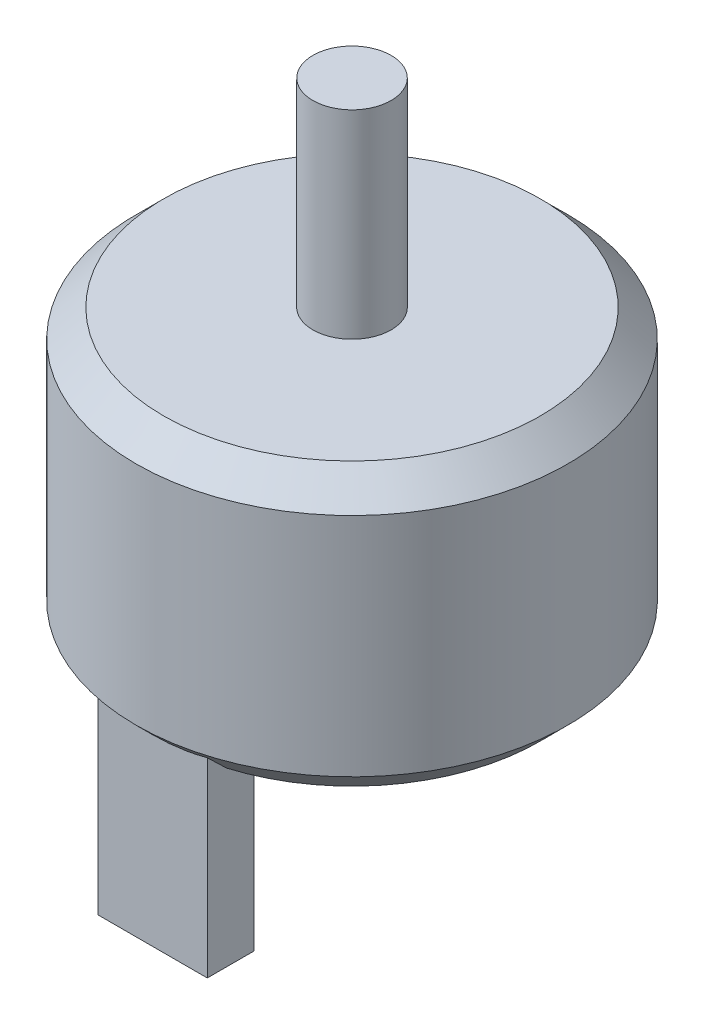
SolidWorks part; units mm, degrees
ref_plane "Front Plane" through (0, 0, 0) normal (0, 0, 1) x (1, 0, 0)
ref_plane "Top Plane" through (0, 0, 0) normal (0, 1, 0) x (1, 0, 0)
ref_plane "Right Plane" through (0, 0, 0) normal (1, 0, 0) x (0, 0, -1)
sketch "Sketch1" plane through (0, 0, 0) normal (0, 1, 0) x (1, 0, 0)
  circle A0 centre (0, 0) radius 13.8
  dimension "D1" = 27.6
extrude "Boss-Extrude1" add sketch "Sketch1" along normal blind 18
sketch "Sketch2" plane through (0, 0, 0) normal (1, 0, 0) x (0, 0, -1)
  line L0 (0, 18) -> (0, 0) construction
  line L1 (13.8, 18) -> (-13.8, 18) construction
  line L2 (12.0322, 18) -> (13.8, 16.2322)
  line L3 (13.8, 0) -> (13.8, 18) construction
  line L4 (12.0322, 18) -> (13.8, 18)
  line L5 (13.8, 18) -> (13.8, 16.2322)
  line L6 (0, 9) -> (13.8, 9) construction
  line L7 (13.8, 0) -> (13.8, 1.7678)
  line L8 (12.0322, 0) -> (13.8, 0)
  line L9 (12.0322, 0) -> (13.8, 1.7678)
  dimension "D1" = 2.5
revolve "Cut-Revolve1" cut sketch "Sketch2" angle 360 about L0
sketch "Sketch3" plane through (0, 18, 0) normal (0, 1, 0) x (1, 0, 0)
  circle A0 centre (0, 0) radius 2.5
  point P0 (0, 0)
  dimension "D1" = 5
extrude "Boss-Extrude2" add sketch "Sketch3" along normal blind 12.7
sketch "Sketch4" plane through (0, 0, 0) normal (0, -1, 0) x (1, 0, 0)
  line L0 (0, 9.75) -> (0, 11.25) construction
  line L2 (-3.5, 12.75) -> (3.5, 12.75)
  line L3 (-3.5, 12.75) -> (-3.5, 9.75)
  line L4 (-3.5, 9.75) -> (3.5, 9.75)
  line L5 (3.5, 12.75) -> (3.5, 9.75)
  line L6 (0, 9.75) -> (0, 12.75) construction
  line L7 (-3.5, 11.25) -> (3.5, 11.25) construction
  circle A0 centre (0, 0) radius 9.75
  point P3 (0, 9.75)
  circle M4 centre (0, 0) radius 12.0322
  dimension "D1" = 19.5
  dimension "D2" = 1.5
  dimension "D3" = 7
  dimension "D4" = 3
extrude "Boss-Extrude3" add sketch "Sketch4" along normal blind 11 and the other way blind 3 contours L5 L2 L3 M4 | L5 L3 L4 M4
